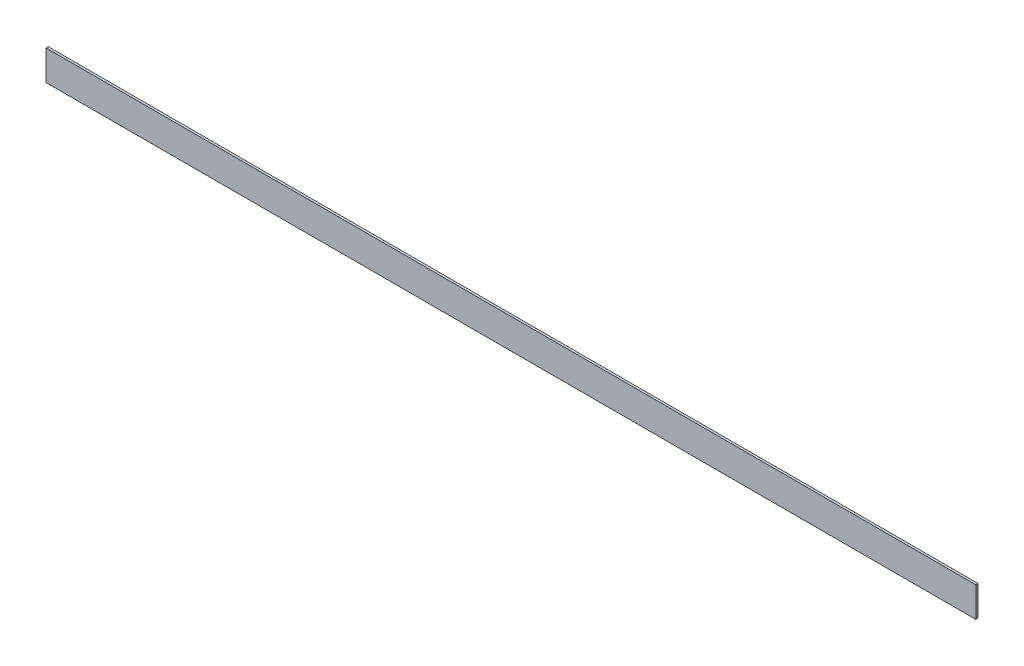
SolidWorks part; units mm, degrees
ref_plane "Front Plane" through (0, 0, 0) normal (0, 0, 1) x (1, 0, 0)
ref_plane "Top Plane" through (0, 0, 0) normal (0, 1, 0) x (1, 0, 0)
ref_plane "Right Plane" through (0, 0, 0) normal (1, 0, 0) x (0, 0, -1)
other "Configuration Table"
sketch "Sketch1" plane through (0, 0, 0) normal (0, 0, 1) x (1, 0, 0)
  line L1 (40, 1132) -> (660, 1132)
  line L2 (40, 1132) -> (40, 1152)
  line L3 (40, 1152) -> (660, 1152)
  line L4 (660, 1132) -> (660, 1152)
extrude "PRESS_uc_rafi_raf_buk_on_1" add sketch "Sketch1" against normal blind 1.5 from offset 20 separate body
